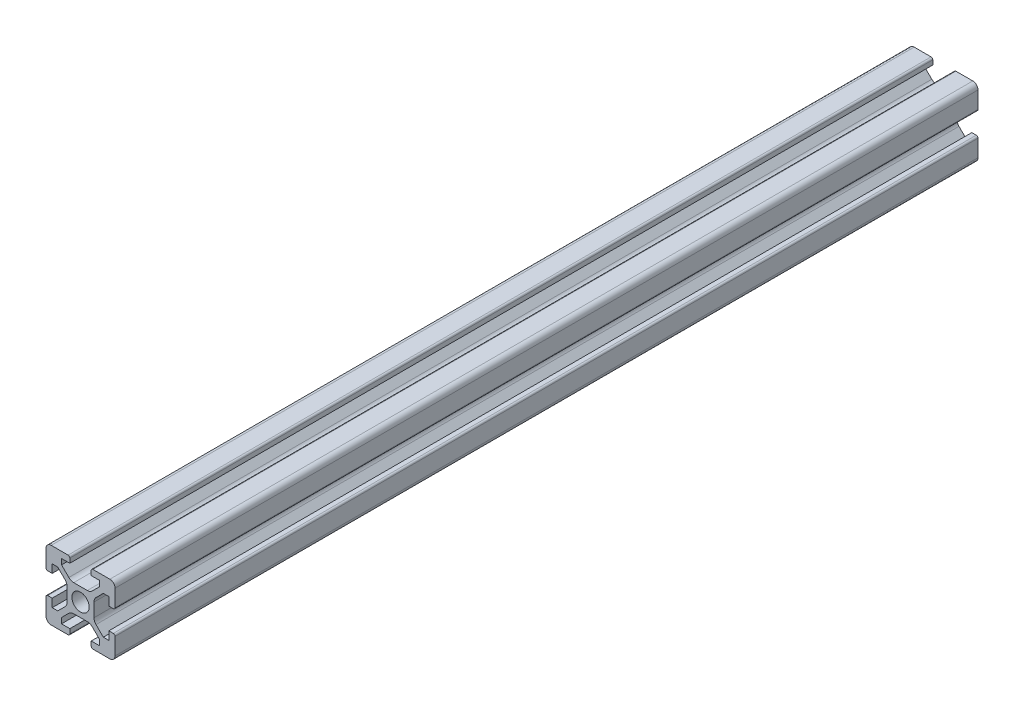
SolidWorks part; units mm, degrees
ref_plane "前视基准面" through (0, 0, 0) normal (0, 0, 1) x (1, 0, 0)
ref_plane "上视基准面" through (0, 0, 0) normal (0, 1, 0) x (1, 0, 0)
ref_plane "右视基准面" through (0, 0, 0) normal (1, 0, 0) x (0, 0, -1)
sketch "草图1" plane through (0, 0, 0) normal (0, 0, 1) x (1, 0, 0)
  line L0 (-19.2539, 0) -> (18.8323, 0) construction
  line L1 (0, 18.4429) -> (0, -19.8143) construction
  line L2 (3.9, 0) -> (3.9, 1.9716)
  line L3 (-8.5, 10) -> (-3.6, 10)
  line L4 (-10, 8.5) -> (-10, 3.6)
  line L5 (-8.5, -10) -> (-3.6, -10)
  line L6 (10, 8.5) -> (10, 3.6)
  line L7 (-10, 10) -> (10, -10) construction
  line L8 (-10, -10) -> (10, 10) construction
  line L9 (4.4858, 3.3858) -> (6.6, 5.5)
  line L10 (6.6, 5.5) -> (8.2, 5.5)
  line L11 (8.2, 5.5) -> (8.2, 3.1)
  line L12 (8.2, 3.1) -> (9.5, 3.1)
  line L17 (8.2, -3.1) -> (9.5, -3.1)
  line L18 (8.2, -5.5) -> (8.2, -3.1)
  line L19 (6.6, -5.5) -> (8.2, -5.5)
  line L20 (4.4858, -3.3858) -> (6.6, -5.5)
  line L21 (3.9, 0) -> (3.9, -1.9716)
  line L22 (10, -3.6) -> (10, -8.5)
  line L23 (-3.1, 8.2) -> (-3.1, 9.5)
  line L24 (-5.5, 8.2) -> (-3.1, 8.2)
  line L25 (-5.5, 6.6) -> (-5.5, 8.2)
  line L26 (-3.3858, 4.4858) -> (-5.5, 6.6)
  line L27 (0, 3.9) -> (-1.9716, 3.9)
  line L28 (0, 3.9) -> (1.9716, 3.9)
  line L29 (3.3858, 4.4858) -> (5.5, 6.6)
  line L30 (5.5, 6.6) -> (5.5, 8.2)
  line L31 (5.5, 8.2) -> (3.1, 8.2)
  line L32 (3.1, 8.2) -> (3.1, 9.5)
  line L33 (3.6, 10) -> (8.5, 10)
  line L34 (-8.2, -3.1) -> (-9.5, -3.1)
  line L35 (-8.2, -5.5) -> (-8.2, -3.1)
  line L36 (-6.6, -5.5) -> (-8.2, -5.5)
  line L37 (-4.4858, -3.3858) -> (-6.6, -5.5)
  line L38 (-3.9, 0) -> (-3.9, -1.9716)
  line L39 (-3.9, 0) -> (-3.9, 1.9716)
  line L40 (-4.4858, 3.3858) -> (-6.6, 5.5)
  line L41 (-6.6, 5.5) -> (-8.2, 5.5)
  line L42 (-8.2, 5.5) -> (-8.2, 3.1)
  line L43 (-8.2, 3.1) -> (-9.5, 3.1)
  line L44 (3.1, -8.2) -> (3.1, -9.5)
  line L45 (5.5, -8.2) -> (3.1, -8.2)
  line L46 (5.5, -6.6) -> (5.5, -8.2)
  line L47 (3.3858, -4.4858) -> (5.5, -6.6)
  line L48 (0, -3.9) -> (1.9716, -3.9)
  line L49 (0, -3.9) -> (-1.9716, -3.9)
  line L50 (-3.3858, -4.4858) -> (-5.5, -6.6)
  line L51 (-5.5, -6.6) -> (-5.5, -8.2)
  line L52 (-5.5, -8.2) -> (-3.1, -8.2)
  line L53 (-3.1, -8.2) -> (-3.1, -9.5)
  line L54 (3.6, -10) -> (8.5, -10)
  line L55 (-10, -3.6) -> (-10, -8.5)
  circle A0 centre (0, 0) radius 2.5
  arc A1 (3.9, 1.9716) -> (4.4858, 3.3858) centre (5.9, 1.9716) cw
  arc A2 (4.4858, -3.3858) -> (3.9, -1.9716) centre (5.9, -1.9716) cw
  arc A5 (10, 8.5) -> (8.5, 10) centre (8.5, 8.5) ccw
  arc A6 (-10, 8.5) -> (-8.5, 10) centre (-8.5, 8.5) cw
  arc A7 (-8.5, -10) -> (-10, -8.5) centre (-8.5, -8.5) cw
  arc A8 (10, -8.5) -> (8.5, -10) centre (8.5, -8.5) cw
  arc A9 (9.5, 3.1) -> (10, 3.6) centre (9.5, 3.6) ccw
  arc A10 (10, -3.6) -> (9.5, -3.1) centre (9.5, -3.6) ccw
  arc A11 (-3.6, 10) -> (-3.1, 9.5) centre (-3.6, 9.5) cw
  arc A12 (-3.3858, 4.4858) -> (-1.9716, 3.9) centre (-1.9716, 5.9) ccw
  arc A13 (1.9716, 3.9) -> (3.3858, 4.4858) centre (1.9716, 5.9) ccw
  arc A14 (3.1, 9.5) -> (3.6, 10) centre (3.6, 9.5) cw
  arc A15 (-10, -3.6) -> (-9.5, -3.1) centre (-9.5, -3.6) cw
  arc A16 (-4.4858, -3.3858) -> (-3.9, -1.9716) centre (-5.9, -1.9716) ccw
  arc A17 (-3.9, 1.9716) -> (-4.4858, 3.3858) centre (-5.9, 1.9716) ccw
  arc A18 (-9.5, 3.1) -> (-10, 3.6) centre (-9.5, 3.6) cw
  arc A19 (3.6, -10) -> (3.1, -9.5) centre (3.6, -9.5) cw
  arc A20 (3.3858, -4.4858) -> (1.9716, -3.9) centre (1.9716, -5.9) ccw
  arc A21 (-1.9716, -3.9) -> (-3.3858, -4.4858) centre (-1.9716, -5.9) ccw
  arc A22 (-3.1, -9.5) -> (-3.6, -10) centre (-3.6, -9.5) cw
  point P34 (3.9, 2.8)
  point P37 (3.9, -2.8)
  point P42 (10, 3.1)
  point P53 (10, -3.1)
  dimension "D1" = 5
  dimension "D10" = 2
  dimension "D13" = 1.5
  dimension "D8" = 0.5
  dimension "D3" = 6.1
  dimension "D4" = 11
  dimension "D5" = 6.2
  dimension "D6" = 1.8
  dimension "D7" = 3.4
  dimension "D16" = 20
extrude "凸台-拉伸1" add sketch "草图1" along normal blind 250
